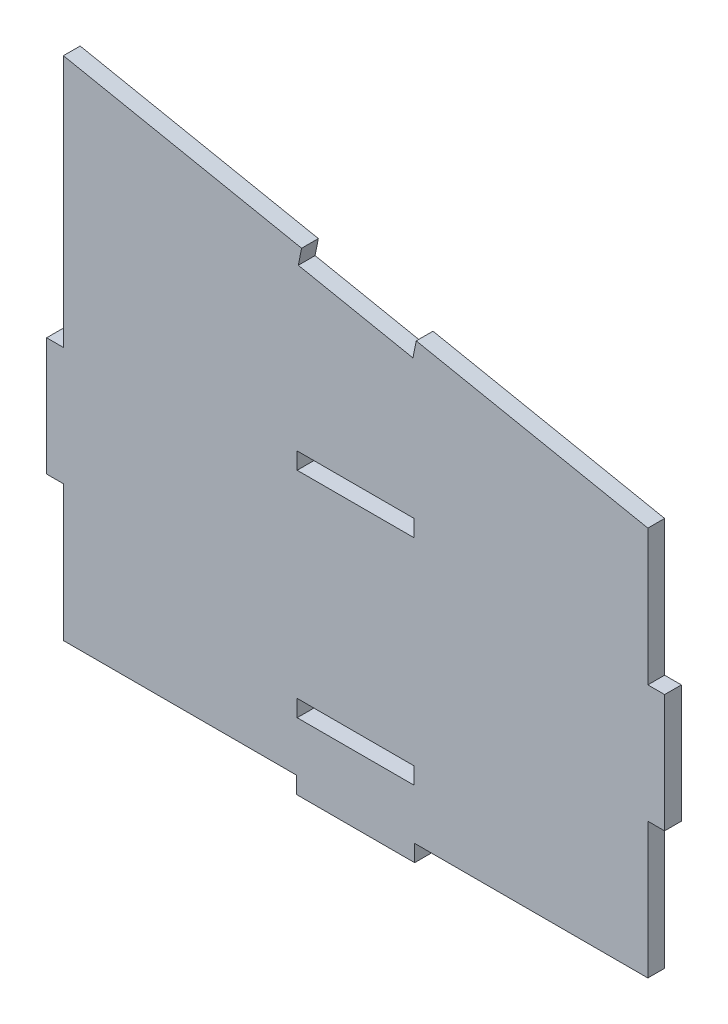
SolidWorks part; units mm, degrees
ref_plane "Front Plane" through (0, 0, 0) normal (0, 0, 1) x (1, 0, 0)
ref_plane "Top Plane" through (0, 0, 0) normal (0, 1, 0) x (1, 0, 0)
ref_plane "Right Plane" through (0, 0, 0) normal (1, 0, 0) x (0, 0, -1)
sketch "Sketch1" plane through (0, 0, 0) normal (0, 0, 1) x (1, 0, 0)
  line L0 (0, 130) -> (0, 65.15)
  line L1 (0, 0) -> (59.85, 0)
  line L2 (150, 0) -> (150, 34.85)
  line L3 (150, 100) -> (90.552, 111.8896)
  line L5 (0, 65.15) -> (-4.3, 65.15)
  line L7 (0, 34.85) -> (-4.3, 34.85)
  line L8 (-4.3, 65.15) -> (-4.3, 34.85)
  line L9 (150, 65.15) -> (154.3, 65.15)
  line L11 (150, 34.85) -> (154.3, 34.85)
  line L12 (154.3, 65.15) -> (154.3, 34.85)
  line L14 (90.15, 0) -> (90.15, -4.3)
  line L15 (90.15, -4.3) -> (59.85, -4.3)
  line L16 (59.85, 0) -> (59.85, -4.3)
  line L17 (90.552, 111.8896) -> (89.7087, 107.6731)
  line L18 (61.1346, 117.7731) -> (60.2913, 113.5566)
  line L19 (89.7087, 107.6731) -> (60.2913, 113.5566)
  line L20 (90.15, 0) -> (150, 0)
  line L21 (150, 65.15) -> (150, 100)
  line L22 (0, 34.85) -> (0, 0)
  line L23 (61.1346, 117.7731) -> (0, 130)
  line L25 (60, 17.15) -> (90, 17.15)
  line L26 (60, 17.15) -> (60, 12.85)
  line L27 (60, 12.85) -> (90, 12.85)
  line L28 (90, 17.15) -> (90, 12.85)
  line L29 (60, 17.15) -> (90, 12.85) construction
  line L30 (60, 12.85) -> (90, 17.15) construction
  line L31 (60, 72.15) -> (90, 72.15)
  line L32 (60, 72.15) -> (60, 67.85)
  line L33 (60, 67.85) -> (90, 67.85)
  line L34 (90, 72.15) -> (90, 67.85)
  line L35 (60, 72.15) -> (90, 67.85) construction
  line L36 (60, 67.85) -> (90, 72.15) construction
  point P17 (75, 110.6148)
  point P20 (75, -4.3)
  point P23 (-4.3, 50)
  point P24 (154.3, 50)
  point P25 (75, 15)
  point P31 (75, 70)
  dimension "D1" = 130
  dimension "D2" = 100
  dimension "D3" = 150
  dimension "D4" = 75
  dimension "D5" = 30.3
  dimension "D6" = 4.3
  dimension "D7" = 50
  dimension "D8" = 30
  dimension "D9" = 4.3
  dimension "D10" = 15
  dimension "D11" = 70
  dimension "D12" = 30
extrude "Boss-Extrude1" add sketch "Sketch1" along normal blind 4.3
